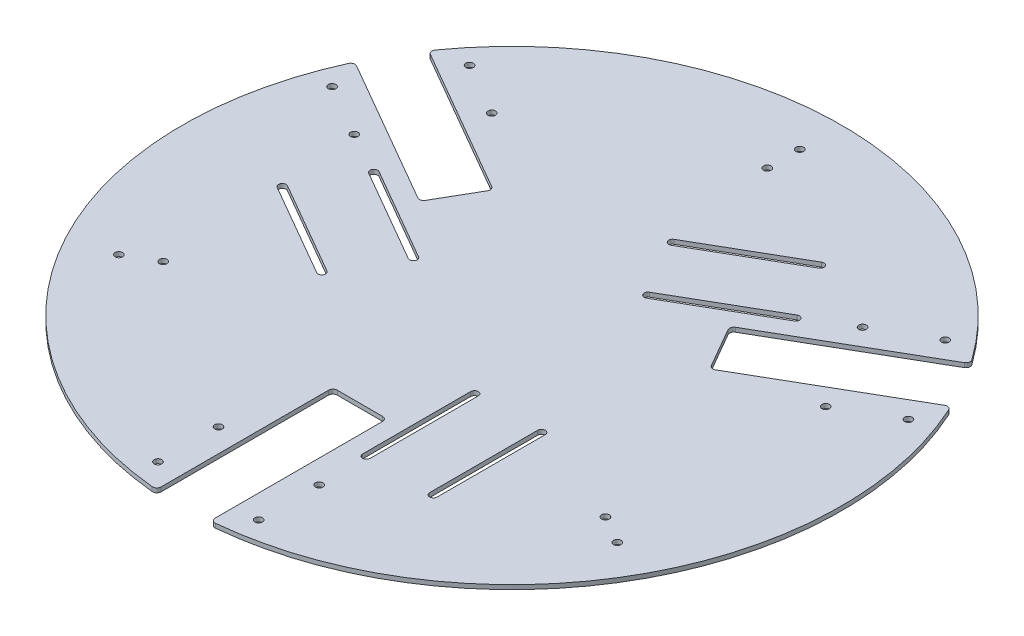
SolidWorks part; units mm, degrees
ref_plane "Front Plane" through (0, 0, 0) normal (0, 0, 1) x (1, 0, 0)
ref_plane "Top Plane" through (0, 0, 0) normal (0, 1, 0) x (1, 0, 0)
ref_plane "Right Plane" through (0, 0, 0) normal (1, 0, 0) x (0, 0, -1)
sketch "Sketch1" plane through (0, 0, 0) normal (0, 1, 0) x (1, 0, 0)
  line L0 (0, 0) -> (0, -100) construction
  line L1 (0, 0) -> (86.6025, 50) construction
  line L2 (0, 0) -> (-132.0689, 76.25) construction
  line L3 (22.66, -89.9999) -> (22.66, -39.9999) construction
  line L4 (20.91, -89.9999) -> (20.91, -39.9999)
  line L5 (24.41, -89.9999) -> (24.41, -39.9999)
  line L9 (-12.5, -149.7999) -> (-12.5, -72.3283)
  line L10 (-10.5, -70.3283) -> (10.5, -70.3283)
  line L11 (12.5, -149.7999) -> (12.5, -72.3283)
  line L12 (135.9805, 64.0746) -> (68.8882, 25.3388)
  line L13 (55.6561, 44.2574) -> (66.1561, 26.0709)
  line L14 (123.4805, 85.7253) -> (56.3882, 46.9895)
  line L21 (-123.4805, 85.7253) -> (-56.3882, 46.9895)
  line L22 (-66.1561, 26.0709) -> (-55.6561, 44.2574)
  line L23 (-135.9805, 64.0746) -> (-68.8882, 25.3388)
  line L30 (38.16, -16.2974) -> (38.16, -83.5714) construction
  line L31 (53.66, -89.9999) -> (53.66, -39.9999) construction
  line L32 (55.41, -89.9999) -> (55.41, -39.9999)
  line L33 (51.91, -89.9999) -> (51.91, -39.9999)
  line L49 (-105.6472, -2.9865) -> (-62.3459, -27.9865)
  line L50 (-103.8972, 0.0446) -> (-60.5959, -24.9554)
  line L55 (-90.1472, 23.8603) -> (-46.8459, -1.1397)
  line L56 (-88.3972, 26.8913) -> (-45.0959, 1.8913)
  line L57 (0, 0) -> (132.0689, -76.25) construction
  line L66 (-89.2722, 25.3758) -> (-45.9709, 0.3758) construction
  line L67 (-104.7722, -1.471) -> (-61.4709, -26.471) construction
  line L68 (50.2372, 92.9864) -> (6.9359, 67.9864)
  line L69 (51.9872, 89.9553) -> (8.6859, 64.9553)
  line L70 (65.7372, 66.1396) -> (22.4359, 41.1396)
  line L71 (67.4872, 63.1085) -> (24.1859, 38.1085)
  line L72 (66.6122, 64.6241) -> (23.3109, 39.6241) construction
  line L73 (51.1122, 91.4709) -> (7.8109, 66.4709) construction
  arc A0 (14.6927, -151.7906) -> (138.8008, 63.171) centre (0, 0) ccw
  arc A1 (20.91, -89.9999) -> (24.41, -89.9999) centre (22.66, -89.9999) ccw
  arc A2 (24.41, -39.9999) -> (20.91, -39.9999) centre (22.66, -39.9999) ccw
  arc A5 (12.5, -72.3283) -> (10.5, -70.3283) centre (10.5, -72.3283) ccw
  arc A6 (-12.5, -72.3283) -> (-10.5, -70.3283) centre (-10.5, -72.3283) cw
  arc A7 (-12.5, -149.7999) -> (-14.6927, -151.7906) centre (-14.5, -149.7999) cw
  arc A8 (12.5, -149.7999) -> (14.6927, -151.7906) centre (14.5, -149.7999) ccw
  arc A9 (123.4805, 85.7253) -> (124.1081, 88.6195) centre (122.4805, 87.4573) ccw
  arc A10 (135.9805, 64.0746) -> (138.8008, 63.171) centre (136.9805, 62.3426) cw
  arc A11 (68.8882, 25.3388) -> (66.1561, 26.0709) centre (67.8882, 27.0709) cw
  arc A12 (56.3882, 46.9895) -> (55.6561, 44.2574) centre (57.3882, 45.2574) ccw
  arc A17 (124.1081, 88.6195) -> (-124.1081, 88.6195) centre (0, 0) ccw
  arc A18 (-123.4805, 85.7253) -> (-124.1081, 88.6195) centre (-122.4805, 87.4573) cw
  arc A19 (-135.9805, 64.0746) -> (-138.8008, 63.171) centre (-136.9805, 62.3426) ccw
  arc A20 (-56.3882, 46.9895) -> (-55.6561, 44.2574) centre (-57.3882, 45.2574) cw
  arc A21 (-68.8882, 25.3388) -> (-66.1561, 26.0709) centre (-67.8882, 27.0709) ccw
  arc A26 (-138.8008, 63.171) -> (-14.6927, -151.7906) centre (0, 0) ccw
  arc A27 (55.41, -89.9999) -> (51.91, -89.9999) centre (53.66, -89.9999) cw
  arc A28 (51.91, -39.9999) -> (55.41, -39.9999) centre (53.66, -39.9999) cw
  circle A65 centre (115.2828, -66.5585) radius 1.75
  circle A66 centre (102.2924, -59.0585) radius 1.75
  circle A67 centre (-115.2828, -66.5585) radius 1.75
  circle A68 centre (-102.2924, -59.0585) radius 1.75
  circle A69 centre (0, 133.1171) radius 1.75
  circle A70 centre (0, 118.1171) radius 1.75
  circle A71 centre (110.0199, 90.4009) radius 1.75
  circle A72 centre (85.7712, 76.4009) radius 1.75
  circle A73 centre (133.2999, 50.0787) radius 1.75
  circle A74 centre (109.0512, 36.0787) radius 1.75
  circle A75 centre (23.28, -140.4804) radius 1.75
  circle A76 centre (23.28, -112.4804) radius 1.75
  circle A77 centre (-23.28, -140.4804) radius 1.75
  circle A78 centre (-23.28, -112.4804) radius 1.75
  arc A79 (-60.5959, -24.9554) -> (-62.3459, -27.9865) centre (-61.4709, -26.471) cw
  arc A80 (-105.6472, -2.9865) -> (-103.8972, 0.0446) centre (-104.7722, -1.471) cw
  arc A81 (-88.3972, 26.8913) -> (-90.1472, 23.8603) centre (-89.2722, 25.3758) ccw
  arc A82 (-46.8459, -1.1397) -> (-45.0959, 1.8913) centre (-45.9709, 0.3758) ccw
  arc A83 (8.6859, 64.9553) -> (6.9359, 67.9864) centre (7.8109, 66.4709) cw
  arc A84 (50.2372, 92.9864) -> (51.9872, 89.9553) centre (51.1122, 91.4709) cw
  arc A85 (67.4872, 63.1085) -> (65.7372, 66.1396) centre (66.6122, 64.6241) ccw
  arc A86 (22.4359, 41.1396) -> (24.1859, 38.1085) centre (23.3109, 39.6241) ccw
  circle A87 centre (-133.2992, 50.0792) radius 1.75
  circle A88 centre (-109.0504, 36.0792) radius 1.75
  circle A89 centre (-110.0192, 90.4013) radius 1.75
  circle A90 centre (-85.7704, 76.4013) radius 1.75
  point P8 (22.66, -64.9999)
  point P13 (12.5, -111.0641)
  point P25 (0, -70.3283)
  point P26 (12.5, -70.3283)
  point P29 (-12.5, -70.3283)
  point P32 (-12.5, -151.9868)
  point P35 (12.5, -151.9868)
  point P57 (-67.6215, 12.8758)
  point P84 (3.5, 0)
  point P85 (-83.1215, -13.971)
  point P92 (53.66, -64.9999)
  point P101 (44.9615, 52.1241)
  point P114 (5.7735, -10)
  point P115 (-9.4108, 16.3)
  point P118 (29.4615, 78.9709)
  point P121 (0, -17.583)
  point P135 (0, 0)
  point P136 (0, 0)
  point P145 (0.0002, -0.0001)
  dimension "D1" = 305
  dimension "D5" = 1.75
  dimension "D7" = 2
  dimension "D8" = 2
  dimension "D11" = 3.5
  dimension "D13" = 3.5
  dimension "D15" = 15
  dimension "D2" = 120
  dimension "D3" = 120
  dimension "D4" = 3
  dimension "D6" = 12.5
  dimension "D9" = 15.5
  dimension "D10" = 10.16
  dimension "D12" = 50
  dimension "D14" = 31
  dimension "D17" = 59.8
  dimension "D16" = 3
  dimension "D18" = 3
extrude "Boss-Extrude1" add sketch "Sketch1" along normal blind 2
